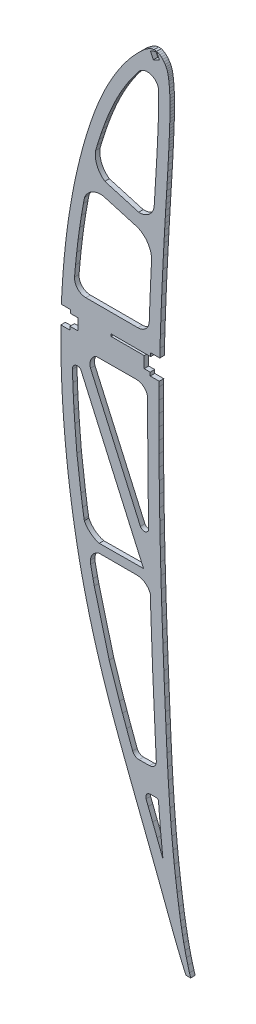
SolidWorks part; units mm, degrees
ref_plane "前视基准面" through (0, 0, 0) normal (0, 0, 1) x (1, 0, 0)
ref_plane "上视基准面" through (0, 0, 0) normal (0, 1, 0) x (1, 0, 0)
ref_plane "右视基准面" through (0, 0, 0) normal (1, 0, 0) x (0, 0, -1)
sketch "Model" plane through (0, 0, 0) normal (0, 0, 1) x (1, 0, 0)
  line L0 (43.8502, 236.8863) -> (43.8502, 237.8863)
  line L1 (43.8502, 237.8863) -> (61.3389, 237.8863)
  line L2 (64.0081, 356.0743) -> (61.2822, 354.8212)
  line L3 (61.2822, 354.8212) -> (62.5342, 352.0962)
  line L4 (62.5342, 352.0962) -> (65.2602, 353.3483)
  line L5 (65.2602, 353.3483) -> (64.0081, 356.0743)
  line L6 (43.8502, 236.8863) -> (58.5041, 236.8863)
  line L7 (30.3743, 274.2028) -> (30.7583, 276.6642)
  line L8 (30.7583, 276.6642) -> (31.6422, 281.7045)
  line L9 (31.6422, 281.7045) -> (32.1282, 284.2535)
  line L10 (37.0281, 304.6188) -> (37.7846, 307.1696)
  line L11 (37.7846, 307.1696) -> (38.5746, 309.7054)
  line L12 (38.5746, 309.7054) -> (39.4005, 312.2239)
  line L13 (39.4005, 312.2239) -> (40.2658, 314.728)
  line L14 (40.2658, 314.728) -> (41.1738, 317.2256)
  line L15 (41.1738, 317.2256) -> (41.6557, 318.4984)
  line L16 (41.6557, 318.4984) -> (42.1518, 319.7735)
  line L17 (42.1518, 319.7735) -> (42.659, 321.038)
  line L18 (42.659, 321.038) -> (43.1794, 322.2948)
  line L19 (43.1794, 322.2948) -> (43.7131, 323.5447)
  line L20 (43.7131, 323.5447) -> (44.2587, 324.7831)
  line L21 (44.2587, 324.7831) -> (44.8177, 326.0086)
  line L22 (44.8177, 326.0086) -> (45.4212, 327.2858)
  line L23 (45.4212, 327.2858) -> (46.0416, 328.5518)
  line L24 (46.0416, 328.5518) -> (46.6795, 329.8082)
  line L25 (46.6795, 329.8082) -> (47.3363, 331.0548)
  line L26 (47.3363, 331.0548) -> (48.0127, 332.2944)
  line L27 (48.0127, 332.2944) -> (48.708, 333.5247)
  line L28 (48.708, 333.5247) -> (49.4244, 334.7466)
  line L29 (49.4244, 334.7466) -> (50.2241, 336.0624)
  line L30 (50.2241, 336.0624) -> (51.0449, 337.3625)
  line L31 (51.0449, 337.3625) -> (51.8842, 338.6419)
  line L32 (51.8842, 338.6419) -> (52.7408, 339.8942)
  line L33 (52.7408, 339.8942) -> (53.6128, 341.1165)
  line L34 (53.6128, 341.1165) -> (54.497, 342.3029)
  line L35 (54.497, 342.3029) -> (55.3966, 343.4556)
  line L36 (55.3966, 343.4556) -> (55.5461, 343.6396)
  line L37 (64.8723, 340.5875) -> (64.8983, 339.5786)
  line L38 (64.8983, 339.5786) -> (64.9145, 338.3543)
  line L39 (64.9145, 338.3543) -> (64.9166, 337.1217)
  line L40 (64.9166, 337.1217) -> (64.906, 335.8858)
  line L41 (64.906, 335.8858) -> (64.8837, 334.6396)
  line L42 (64.8837, 334.6396) -> (64.8535, 333.3874)
  line L43 (64.8535, 333.3874) -> (64.8152, 332.1288)
  line L44 (64.8152, 332.1288) -> (64.7717, 330.8612)
  line L45 (64.7717, 330.8612) -> (64.725, 329.5861)
  line L46 (64.725, 329.5861) -> (64.6763, 328.3074)
  line L47 (64.6763, 328.3074) -> (64.6257, 327.0298)
  line L48 (64.6257, 327.0298) -> (64.573, 325.752)
  line L49 (64.573, 325.752) -> (64.5184, 324.4741)
  line L50 (64.5184, 324.4741) -> (64.4618, 323.1981)
  line L51 (64.4618, 323.1981) -> (64.4021, 321.9181)
  line L52 (64.4021, 321.9181) -> (64.3417, 320.6445)
  line L53 (64.3417, 320.6445) -> (64.2118, 318.0866)
  line L54 (64.2118, 318.0866) -> (64.0727, 315.5278)
  line L55 (64.0727, 315.5278) -> (63.9275, 312.9667)
  line L56 (63.9275, 312.9667) -> (63.776, 310.4033)
  line L57 (63.776, 310.4033) -> (63.6213, 307.8329)
  line L58 (63.6213, 307.8329) -> (63.4646, 305.2646)
  line L59 (63.4646, 305.2646) -> (63.3068, 302.693)
  line L60 (63.3068, 302.693) -> (63.1507, 300.1159)
  line L61 (63.1507, 300.1159) -> (62.9956, 297.5408)
  line L62 (62.9956, 297.5408) -> (62.9036, 296.0125)
  line L63 (61.7232, 274.3337) -> (61.4776, 269.1775)
  line L64 (61.4776, 269.1775) -> (61.248, 264.0195)
  line L65 (61.248, 264.0195) -> (61.0335, 258.8612)
  line L66 (61.0335, 258.8612) -> (60.73, 250.9656)
  line L67 (55.7337, 246.1577) -> (32.7075, 246.1577)
  line L68 (27.7263, 251.5905) -> (28.1424, 256.3804)
  line L69 (28.1424, 256.3804) -> (28.6669, 261.4747)
  line L70 (28.6669, 261.4747) -> (29.2751, 266.5542)
  line L71 (29.2751, 266.5542) -> (29.9709, 271.6178)
  line L72 (29.9709, 271.6178) -> (30.3743, 274.2028)
  line L73 (60.0666, 221.0284) -> (60.0507, 218.0131)
  line L74 (60.0507, 218.0131) -> (60.0407, 212.8556)
  line L75 (31.9099, 161.1417) -> (31.2714, 165.2332)
  line L76 (31.2714, 165.2332) -> (30.5486, 170.2849)
  line L77 (27.3053, 203.7804) -> (27.1958, 205.6541)
  line L78 (27.1958, 205.6541) -> (26.963, 210.7202)
  line L79 (26.963, 210.7202) -> (26.792, 215.7946)
  line L80 (37.2928, 225.962) -> (55.0468, 226.0546)
  line L81 (41.1027, 294.8752) -> (56.0899, 290.5602)
  line L82 (40.2635, 288.952) -> (55.5929, 284.5226)
  line L83 (21.9141, 238.2148) -> (22.049, 241.3454)
  line L84 (22.049, 241.3454) -> (22.3423, 246.4791)
  line L85 (22.3423, 246.4791) -> (22.7143, 251.6692)
  line L86 (22.7143, 251.6692) -> (23.1646, 256.8528)
  line L87 (23.1646, 256.8528) -> (23.6974, 262.028)
  line L88 (23.6974, 262.028) -> (24.3157, 267.1919)
  line L89 (24.3157, 267.1919) -> (25.0237, 272.3436)
  line L90 (25.0237, 272.3436) -> (25.8253, 277.4815)
  line L91 (25.8253, 277.4815) -> (26.7237, 282.6046)
  line L92 (26.7237, 282.6046) -> (27.2214, 285.2147)
  line L93 (27.2214, 285.2147) -> (27.7453, 287.8191)
  line L94 (27.7453, 287.8191) -> (28.2964, 290.4176)
  line L95 (28.2964, 290.4176) -> (28.8739, 293.0092)
  line L96 (28.8739, 293.0092) -> (29.4797, 295.5951)
  line L97 (29.4797, 295.5951) -> (30.1128, 298.1752)
  line L98 (30.1128, 298.1752) -> (30.7752, 300.7485)
  line L99 (30.7752, 300.7485) -> (31.4839, 303.383)
  line L100 (31.4839, 303.383) -> (32.2251, 306.0088)
  line L101 (32.2251, 306.0088) -> (33.0008, 308.6241)
  line L102 (33.0008, 308.6241) -> (33.8119, 311.228)
  line L103 (33.8119, 311.228) -> (34.6617, 313.8195)
  line L104 (34.6617, 313.8195) -> (35.5531, 316.3988)
  line L105 (35.5531, 316.3988) -> (36.486, 318.965)
  line L106 (36.486, 318.965) -> (36.9877, 320.2901)
  line L107 (36.9877, 320.2901) -> (37.5016, 321.6108)
  line L108 (37.5016, 321.6108) -> (38.0287, 322.925)
  line L109 (38.0287, 322.925) -> (38.5702, 324.2329)
  line L110 (38.5702, 324.2329) -> (39.126, 325.5344)
  line L111 (39.126, 325.5344) -> (39.6961, 326.8285)
  line L112 (39.6961, 326.8285) -> (40.2825, 328.1143)
  line L113 (40.2825, 328.1143) -> (40.9157, 329.4542)
  line L114 (40.9157, 329.4542) -> (41.5673, 330.7839)
  line L115 (41.5673, 330.7839) -> (42.2383, 332.1054)
  line L116 (42.2383, 332.1054) -> (42.9297, 333.4178)
  line L117 (42.9297, 333.4178) -> (43.6415, 334.7221)
  line L118 (43.6415, 334.7221) -> (44.3746, 336.0193)
  line L119 (44.3746, 336.0193) -> (45.1311, 337.3095)
  line L120 (45.1311, 337.3095) -> (45.9734, 338.6956)
  line L121 (45.9734, 338.6956) -> (46.8403, 340.0687)
  line L122 (46.8403, 340.0687) -> (47.73, 341.4248)
  line L123 (47.73, 341.4248) -> (48.6417, 342.7579)
  line L124 (48.6417, 342.7579) -> (49.5727, 344.0627)
  line L125 (49.5727, 344.0627) -> (50.5211, 345.3353)
  line L126 (50.5211, 345.3353) -> (51.4851, 346.5705)
  line L127 (51.4851, 346.5705) -> (52.0855, 347.3094)
  line L128 (52.0855, 347.3094) -> (52.6963, 348.0377)
  line L129 (52.6963, 348.0377) -> (53.3233, 348.7618)
  line L130 (53.3233, 348.7618) -> (53.9704, 349.4847)
  line L131 (53.9704, 349.4847) -> (54.6442, 350.2148)
  line L132 (54.6442, 350.2148) -> (55.3486, 350.9552)
  line L133 (55.3486, 350.9552) -> (56.0902, 351.7123)
  line L134 (56.0902, 351.7123) -> (57.1238, 352.7303)
  line L135 (57.1238, 352.7303) -> (58.2146, 353.7229)
  line L136 (58.2146, 353.7229) -> (59.3482, 354.6282)
  line L137 (59.3482, 354.6282) -> (60.5114, 355.3816)
  line L138 (60.5114, 355.3816) -> (61.688, 355.9205)
  line L139 (61.688, 355.9205) -> (62.8648, 356.181)
  line L140 (62.8648, 356.181) -> (64.0263, 356.1016)
  line L141 (64.0263, 356.1016) -> (64.7387, 355.8565)
  line L142 (64.7387, 355.8565) -> (65.4281, 355.4732)
  line L143 (65.4281, 355.4732) -> (66.0854, 354.9754)
  line L144 (66.0854, 354.9754) -> (66.7009, 354.3817)
  line L145 (66.7009, 354.3817) -> (67.2626, 353.7135)
  line L146 (67.2626, 353.7135) -> (67.7605, 352.9935)
  line L147 (67.7605, 352.9935) -> (68.1837, 352.2403)
  line L148 (68.1837, 352.2403) -> (68.4927, 351.5601)
  line L149 (68.4927, 351.5601) -> (68.7419, 350.8723)
  line L150 (68.7419, 350.8723) -> (68.9424, 350.1774)
  line L151 (68.9424, 350.1774) -> (69.1011, 349.4777)
  line L152 (69.1011, 349.4777) -> (69.2269, 348.7735)
  line L153 (69.2269, 348.7735) -> (69.329, 348.0643)
  line L154 (69.329, 348.0643) -> (69.4141, 347.3533)
  line L155 (69.4141, 347.3533) -> (69.5467, 346.0819)
  line L156 (69.5467, 346.0819) -> (69.6564, 344.8065)
  line L157 (69.6564, 344.8065) -> (69.7453, 343.5271)
  line L158 (69.7453, 343.5271) -> (69.8143, 342.2449)
  line L159 (69.8143, 342.2449) -> (69.8643, 340.9609)
  line L160 (69.8643, 340.9609) -> (69.8974, 339.6761)
  line L161 (69.8974, 339.6761) -> (69.9144, 338.3916)
  line L162 (69.9144, 338.3916) -> (69.9166, 337.1045)
  line L163 (69.9166, 337.1045) -> (69.9056, 335.8198)
  line L164 (69.9056, 335.8198) -> (69.8827, 334.5345)
  line L165 (69.8827, 334.5345) -> (69.8516, 333.251)
  line L166 (69.8516, 333.251) -> (69.8126, 331.967)
  line L167 (69.8126, 331.967) -> (69.7685, 330.6839)
  line L168 (69.7685, 330.6839) -> (69.7215, 329.3996)
  line L169 (69.7215, 329.3996) -> (69.6726, 328.1133)
  line L170 (69.6726, 328.1133) -> (69.6216, 326.8278)
  line L171 (69.6216, 326.8278) -> (69.5686, 325.5423)
  line L172 (69.5686, 325.5423) -> (69.5136, 324.2567)
  line L173 (69.5136, 324.2567) -> (69.4566, 322.971)
  line L174 (69.4566, 322.971) -> (69.3967, 321.6851)
  line L175 (69.3967, 321.6851) -> (69.3357, 320.3992)
  line L176 (69.3357, 320.3992) -> (69.2049, 317.8241)
  line L177 (69.2049, 317.8241) -> (69.065, 315.2505)
  line L178 (69.065, 315.2505) -> (68.9191, 312.6777)
  line L179 (68.9191, 312.6777) -> (68.7672, 310.1056)
  line L180 (68.7672, 310.1056) -> (68.6123, 307.5324)
  line L181 (68.6123, 307.5324) -> (68.4553, 304.9601)
  line L182 (68.4553, 304.9601) -> (68.2974, 302.3868)
  line L183 (68.2974, 302.3868) -> (68.1415, 299.8136)
  line L184 (68.1415, 299.8136) -> (67.9866, 297.2403)
  line L185 (67.9866, 297.2403) -> (67.8337, 294.6672)
  line L186 (67.8337, 294.6672) -> (67.6837, 292.0952)
  line L187 (67.6837, 292.0952) -> (67.5358, 289.5223)
  line L188 (67.5358, 289.5223) -> (67.391, 286.9486)
  line L189 (67.391, 286.9486) -> (67.2491, 284.3739)
  line L190 (67.2491, 284.3739) -> (66.9762, 279.2311)
  line L191 (66.9762, 279.2311) -> (66.7172, 274.0889)
  line L192 (66.7172, 274.0889) -> (66.4723, 268.9474)
  line L193 (66.4723, 268.9474) -> (66.2434, 263.8045)
  line L194 (66.2434, 263.8045) -> (66.0295, 258.6613)
  line L195 (66.0295, 258.6613) -> (65.8318, 253.5167)
  line L196 (65.8318, 253.5167) -> (65.6501, 248.3699)
  line L197 (65.6501, 248.3699) -> (65.4861, 243.2309)
  line L198 (65.4861, 243.2309) -> (65.3793, 239.3856)
  line L199 (65.1461, 230.3864) -> (65.1209, 228.2739)
  line L200 (65.1209, 228.2739) -> (65.0778, 223.1351)
  line L201 (65.0778, 223.1351) -> (65.0507, 217.9951)
  line L202 (65.0507, 217.9951) -> (65.0407, 212.854)
  line L203 (65.0407, 212.854) -> (65.0474, 207.7189)
  line L204 (65.0474, 207.7189) -> (65.069, 202.5855)
  line L205 (65.069, 202.5855) -> (65.1067, 197.453)
  line L206 (65.1067, 197.453) -> (65.1593, 192.3204)
  line L207 (65.1593, 192.3204) -> (65.2259, 187.1885)
  line L208 (65.2259, 187.1885) -> (65.3066, 182.0553)
  line L209 (65.3066, 182.0553) -> (65.4004, 176.9209)
  line L210 (65.4004, 176.9209) -> (65.5061, 171.7901)
  line L211 (65.5061, 171.7901) -> (65.6246, 166.661)
  line L212 (65.6246, 166.661) -> (65.7541, 161.5325)
  line L213 (65.7541, 161.5325) -> (65.8956, 156.4056)
  line L214 (65.8956, 156.4056) -> (66.0491, 151.2784)
  line L215 (66.0491, 151.2784) -> (66.2146, 146.1509)
  line L216 (66.2146, 146.1509) -> (66.3903, 141.0219)
  line L217 (66.3903, 141.0219) -> (66.5768, 135.8945)
  line L218 (66.5768, 135.8945) -> (66.7733, 130.7696)
  line L219 (66.7733, 130.7696) -> (66.9786, 125.6462)
  line L220 (66.9786, 125.6462) -> (67.191, 120.5232)
  line L221 (67.191, 120.5232) -> (67.4094, 115.3995)
  line L222 (67.4094, 115.3995) -> (67.6328, 110.2751)
  line L223 (67.6328, 110.2751) -> (67.8604, 105.1489)
  line L224 (67.8604, 105.1489) -> (68.0929, 100.023)
  line L225 (68.0929, 100.023) -> (68.3334, 94.8995)
  line L226 (68.3334, 94.8995) -> (68.5867, 89.7777)
  line L227 (68.5867, 89.7777) -> (68.861, 84.657)
  line L228 (68.861, 84.657) -> (69.1603, 79.5387)
  line L229 (69.1603, 79.5387) -> (69.4905, 74.4211)
  line L230 (69.4905, 74.4211) -> (69.8587, 69.3045)
  line L231 (69.8587, 69.3045) -> (70.2683, 64.1832)
  line L232 (70.2683, 64.1832) -> (70.7236, 59.0673)
  line L233 (70.7236, 59.0673) -> (71.2277, 53.9571)
  line L234 (71.2277, 53.9571) -> (71.7816, 48.8516)
  line L235 (71.7816, 48.8516) -> (72.3913, 43.7511)
  line L236 (72.3913, 43.7511) -> (73.0579, 38.6557)
  line L237 (73.0579, 38.6557) -> (73.7843, 33.5645)
  line L238 (73.7843, 33.5645) -> (74.1753, 31.0039)
  line L239 (74.1753, 31.0039) -> (74.5862, 28.4464)
  line L240 (74.5862, 28.4464) -> (75.0248, 25.8954)
  line L241 (75.0248, 25.8954) -> (75.4931, 23.35)
  line L242 (75.4931, 23.35) -> (75.999, 20.8136)
  line L243 (75.999, 20.8136) -> (76.5465, 18.2865)
  line L244 (76.5465, 18.2865) -> (77.1405, 15.77)
  line L245 (77.1405, 15.77) -> (77.7975, 13.2168)
  line L246 (77.7975, 13.2168) -> (78.4999, 10.676)
  line L247 (78.4999, 10.676) -> (79.0435, 8.9378)
  line L248 (79.0435, 8.9378) -> (76.9392, 8.9378)
  line L249 (76.9392, 8.9378) -> (76.2151, 10.5563)
  line L250 (76.2151, 10.5563) -> (75.1362, 13.0756)
  line L251 (75.1362, 13.0756) -> (74.079, 15.6042)
  line L252 (74.079, 15.6042) -> (73.0623, 18.1028)
  line L253 (73.0623, 18.1028) -> (72.0663, 20.6096)
  line L254 (72.0663, 20.6096) -> (71.088, 23.1224)
  line L255 (71.088, 23.1224) -> (70.1224, 25.6409)
  line L256 (70.1224, 25.6409) -> (69.1646, 28.1628)
  line L257 (69.1646, 28.1628) -> (68.2108, 30.6859)
  line L258 (68.2108, 30.6859) -> (67.2568, 33.211)
  line L259 (67.2568, 33.211) -> (65.3393, 38.2537)
  line L260 (65.3393, 38.2537) -> (63.4101, 43.2897)
  line L261 (63.4101, 43.2897) -> (61.4703, 48.3202)
  line L262 (61.4703, 48.3202) -> (59.5226, 53.3472)
  line L263 (59.5226, 53.3472) -> (57.5699, 58.3729)
  line L264 (57.5699, 58.3729) -> (55.6163, 63.3987)
  line L265 (55.6163, 63.3987) -> (53.6625, 68.4274)
  line L266 (53.6625, 68.4274) -> (51.724, 73.4318)
  line L267 (51.724, 73.4318) -> (49.7993, 78.4411)
  line L268 (49.7993, 78.4411) -> (47.8982, 83.4576)
  line L269 (47.8982, 83.4576) -> (46.0306, 88.486)
  line L270 (46.0306, 88.486) -> (44.2051, 93.5296)
  line L271 (44.2051, 93.5296) -> (42.4317, 98.5931)
  line L272 (42.4317, 98.5931) -> (40.7212, 103.6791)
  line L273 (40.7212, 103.6791) -> (39.1144, 108.6785)
  line L274 (39.1144, 108.6785) -> (37.5787, 113.6988)
  line L275 (37.5787, 113.6988) -> (36.1139, 118.74)
  line L276 (36.1139, 118.74) -> (34.7212, 123.8021)
  line L277 (34.7212, 123.8021) -> (33.4034, 128.8832)
  line L278 (33.4034, 128.8832) -> (32.1588, 133.9844)
  line L279 (32.1588, 133.9844) -> (30.9911, 139.1047)
  line L280 (30.9911, 139.1047) -> (29.9163, 144.157)
  line L281 (29.9163, 144.157) -> (28.9149, 149.2233)
  line L282 (28.9149, 149.2233) -> (27.9849, 154.3014)
  line L283 (27.9849, 154.3014) -> (27.1224, 159.3922)
  line L284 (27.1224, 159.3922) -> (26.3263, 164.4936)
  line L285 (26.3263, 164.4936) -> (25.5947, 169.6065)
  line L286 (25.5947, 169.6065) -> (24.9248, 174.7288)
  line L287 (24.9248, 174.7288) -> (24.3191, 179.8275)
  line L288 (24.3191, 179.8275) -> (23.7734, 184.9305)
  line L289 (23.7734, 184.9305) -> (23.2884, 190.0387)
  line L290 (23.2884, 190.0387) -> (22.8643, 195.1523)
  line L291 (22.8643, 195.1523) -> (22.502, 200.2702)
  line L292 (22.502, 200.2702) -> (22.2025, 205.3935)
  line L293 (22.2025, 205.3935) -> (21.9668, 210.5212)
  line L294 (21.9668, 210.5212) -> (21.7938, 215.6584)
  line L295 (21.7938, 215.6584) -> (21.6867, 220.7971)
  line L296 (21.6867, 220.7971) -> (21.6458, 225.9354)
  line L297 (21.6458, 225.9354) -> (21.6684, 230.2162)
  line L298 (64.8348, 69.4576) -> (64.8725, 68.9337)
  line L299 (64.8725, 68.9337) -> (64.8737, 68.9178)
  line L300 (64.8737, 68.9178) -> (65.286, 63.7622)
  line L301 (65.286, 63.7622) -> (65.7454, 58.6002)
  line L302 (65.7454, 58.6002) -> (66.2542, 53.442)
  line L303 (66.2542, 53.442) -> (66.8024, 48.3895)
  line L304 (66.8024, 48.3895) -> (66.134, 50.1229)
  line L305 (66.134, 50.1229) -> (64.1848, 55.1536)
  line L306 (64.1848, 55.1536) -> (62.2305, 60.1837)
  line L307 (62.2305, 60.1837) -> (60.2765, 65.2102)
  line L308 (60.2765, 65.2102) -> (59.3349, 67.6338)
  line L309 (61.1782, 70.358) -> (63.8269, 70.3858)
  line L310 (31.9099, 161.1417) -> (32.0372, 160.476)
  line L311 (43.0404, 112.5915) -> (47.5508, 99.1034)
  line L312 (38.6326, 155.1014) -> (58.2002, 155.2531)
  line L313 (28.7514, 184.6643) -> (27.8497, 195.5355)
  line L314 (27.8497, 195.5355) -> (27.4917, 200.5926)
  line L315 (60.1139, 196.7245) -> (60.1596, 192.2623)
  line L316 (60.1596, 192.2623) -> (60.2264, 187.1167)
  line L317 (60.2264, 187.1167) -> (60.3074, 181.9704)
  line L318 (60.3074, 181.9704) -> (60.4014, 176.8238)
  line L319 (60.4014, 176.8238) -> (60.5073, 171.6809)
  line L320 (27.3053, 203.7804) -> (27.4917, 200.5926)
  line L321 (36.4497, 137.6568) -> (35.8741, 140.1808)
  line L322 (35.8741, 140.1808) -> (34.8144, 145.162)
  line L323 (34.8144, 145.162) -> (34.7356, 146.6627)
  line L324 (61.2174, 146.9839) -> (61.3934, 140.8454)
  line L325 (61.3934, 140.8454) -> (61.5803, 135.7078)
  line L326 (61.5803, 135.7078) -> (62.2922, 117.1344)
  line L327 (63.2187, 97.2256) -> (63.3391, 94.6588)
  line L328 (63.3391, 94.6588) -> (63.8527, 84.2773)
  line L329 (60.8877, 81.1293) -> (56.2323, 81.0805)
  line L330 (53.3886, 83.0358) -> (50.725, 90.2073)
  line L331 (50.725, 90.2073) -> (48.9155, 95.2069)
  line L332 (48.9155, 95.2069) -> (47.5508, 99.1034)
  line L333 (29.2591, 236.7162) -> (29.1691, 236.7162)
  line L334 (28.1691, 236.7162) -> (29.1691, 236.7162)
  line L335 (29.2591, 236.7162) -> (29.2591, 231.7162)
  line L336 (29.2591, 231.7162) -> (25.6764, 231.7162)
  line L337 (58.5041, 231.8863) -> (61.164, 231.8863)
  line L338 (58.5041, 236.8863) -> (58.5041, 231.8863)
  line L339 (21.6684, 230.2162) -> (25.6764, 230.2162)
  line L340 (25.6764, 231.7162) -> (25.6764, 230.2162)
  line L341 (21.9141, 238.2148) -> (25.8496, 238.2148)
  line L342 (25.8496, 236.7162) -> (25.8496, 238.2148)
  line L343 (25.8496, 236.7162) -> (28.1691, 236.7162)
  line L344 (65.1461, 230.3864) -> (61.164, 230.3864)
  line L345 (61.164, 231.8863) -> (61.164, 230.3864)
  line L346 (65.3793, 239.3856) -> (61.3389, 239.3856)
  line L347 (61.3389, 237.8863) -> (61.3389, 239.3856)
  line L348 (28.7514, 184.6643) -> (30.5486, 170.2849)
  line L349 (36.4497, 137.6568) -> (43.0404, 112.5915)
  line L350 (62.2922, 117.1344) -> (63.2187, 97.2256)
  line L351 (60.1139, 196.7245) -> (60.0407, 212.8556)
  line L352 (56.8072, 170.6744) -> (34.7556, 220.2031)
  line L353 (58.2002, 155.2531) -> (30.3648, 217.7724)
  line L354 (55.3091, 151.2759) -> (38.6326, 151.2759)
  arc A0 (60.0666, 221.0284) -> (55.0468, 226.0546) centre (55.0667, 221.0547) ccw
  arc A1 (64.8723, 340.5875) -> (55.5461, 343.6396) centre (59.9098, 341.1985) ccw
  arc A2 (37.0281, 304.6188) -> (41.1027, 294.8752) centre (46.8581, 303.0058) ccw
  arc A3 (40.2635, 288.952) -> (32.1282, 284.2535) centre (39.2533, 281.3087) ccw
  arc A4 (56.0899, 290.5602) -> (62.9036, 296.0125) centre (56.4727, 297.0655) ccw
  arc A5 (61.7232, 274.3337) -> (55.5929, 284.5226) centre (51.7067, 275.2457) ccw
  arc A6 (32.0372, 160.476) -> (38.6326, 155.1014) centre (41.3268, 165.1417) ccw
  arc A7 (38.6326, 151.2759) -> (34.7356, 146.6627) centre (39.8182, 146.3217) ccw
  arc A8 (61.2174, 146.9839) -> (55.3091, 151.2759) centre (55.2854, 145.0306) ccw
  arc A9 (56.8072, 170.6744) -> (60.5073, 171.6809) centre (58.5406, 171.6062) ccw
  arc A10 (37.2928, 225.962) -> (34.7556, 220.2031) centre (39.2904, 221.6435) ccw
  arc A11 (30.3648, 217.7724) -> (26.792, 215.7946) centre (29.0134, 215.9978) ccw
  arc A12 (55.7337, 246.1577) -> (60.73, 250.9656) centre (55.7337, 251.1577) ccw
  arc A13 (27.7263, 251.5905) -> (32.7075, 246.1577) centre (32.7075, 251.1577) ccw
  arc A14 (61.1782, 70.358) -> (59.3349, 67.6338) centre (61.1991, 68.3581) ccw
  arc A15 (64.8348, 69.4576) -> (63.8269, 70.3858) centre (63.8374, 69.3858) ccw
  arc A16 (60.8877, 81.1293) -> (63.8527, 84.2773) centre (60.8563, 84.1291) ccw
  arc A17 (53.3886, 83.0358) -> (56.2323, 81.0805) centre (56.2009, 84.0804) ccw
extrude "凸台-拉伸1" add sketch "Model" along normal blind 2
